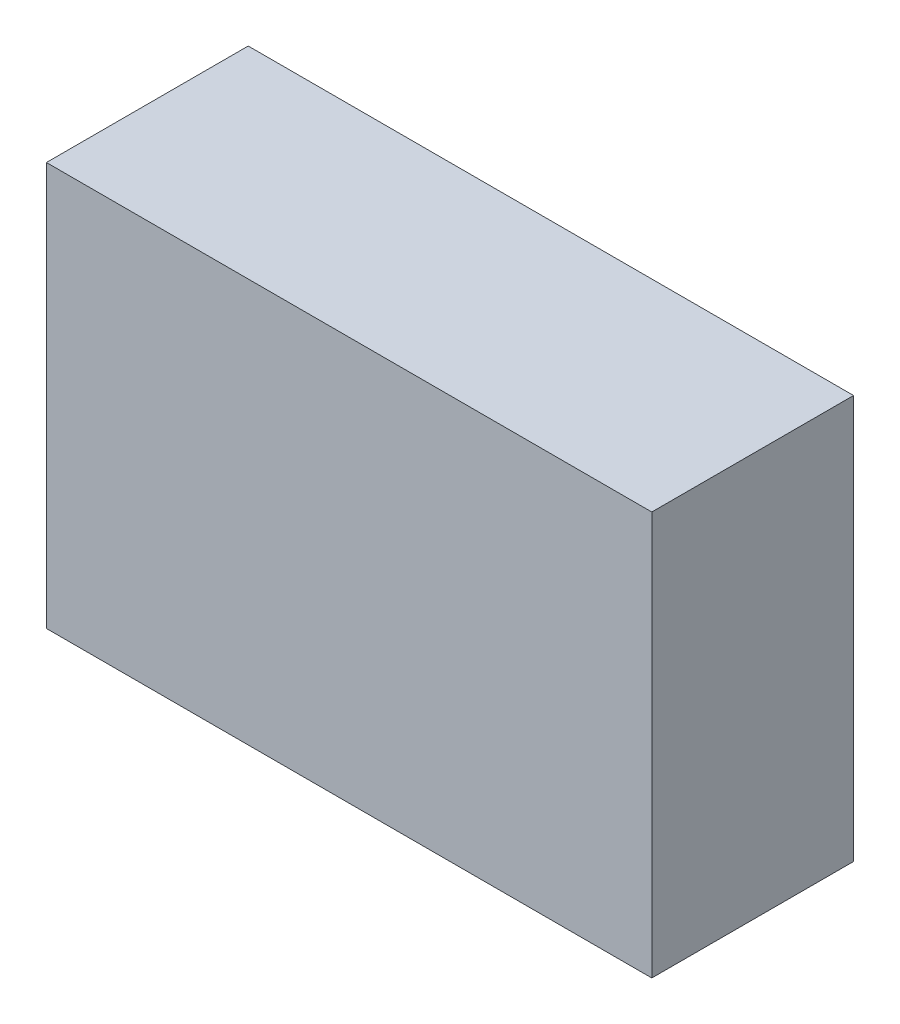
SolidWorks part; units mm, degrees
ref_plane "Front Plane" through (0, 0, 0) normal (0, 0, 1) x (1, 0, 0)
ref_plane "Top Plane" through (0, 0, 0) normal (0, 1, 0) x (1, 0, 0)
ref_plane "Right Plane" through (0, 0, 0) normal (1, 0, 0) x (0, 0, -1)
sketch "Sketch1" plane through (0, 0, 0) normal (0, 0, 1) x (1, 0, 0)
  line L1 (-7.5, -5) -> (7.5, -5)
  line L2 (-7.5, -5) -> (-7.5, 5)
  line L3 (-7.5, 5) -> (7.5, 5)
  line L4 (7.5, -5) -> (7.5, 5)
  line L5 (-7.5, -5) -> (7.5, 5) construction
  line L6 (-7.5, 5) -> (7.5, -5) construction
  point P0 (0, 0)
extrude "Boss-Extrude1" add sketch "Sketch1" against normal blind 5
